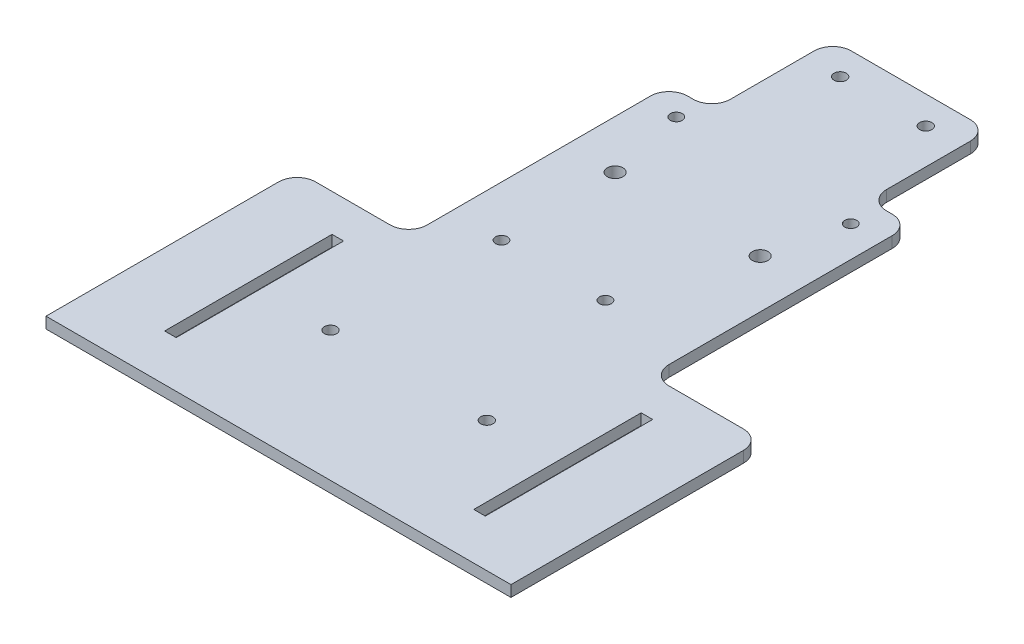
SolidWorks part; units mm, degrees
material "Balsa"
ref_plane "Front Plane" through (0, 0, 0) normal (0, 0, 1) x (1, 0, 0)
ref_plane "Top Plane" through (0, 0, 0) normal (0, 1, 0) x (1, 0, 0)
ref_plane "Right Plane" through (0, 0, 0) normal (1, 0, 0) x (0, 0, -1)
sketch "Sketch1" plane through (0, 0, 0) normal (0, 1, 0) x (1, 0, 0)
  line L0 (-41.55, -50) -> (41.55, -50) construction
  line L1 (-90, -85) -> (90, -85)
  line L2 (-90, -85) -> (-90, 85)
  line L3 (-90, 85) -> (90, 85)
  line L4 (90, -85) -> (90, 85)
  line L5 (-90, -85) -> (90, 85) construction
  line L6 (-90, 85) -> (90, -85) construction
  line L7 (0, -50) -> (0, 0) construction
  line L8 (40, -72.5) -> (43.1, -72.5)
  line L9 (40, -72.5) -> (40, -27.5)
  line L10 (40, -27.5) -> (43.1, -27.5)
  line L11 (43.1, -72.5) -> (43.1, -27.5)
  line L12 (40, -72.5) -> (43.1, -27.5) construction
  line L13 (40, -27.5) -> (43.1, -72.5) construction
  line L14 (-43.1, -72.5) -> (-40, -72.5)
  line L15 (-43.1, -72.5) -> (-43.1, -27.5)
  line L16 (-43.1, -27.5) -> (-40, -27.5)
  line L17 (-40, -72.5) -> (-40, -27.5)
  line L18 (-43.1, -72.5) -> (-40, -27.5) construction
  line L19 (-43.1, -27.5) -> (-40, -72.5) construction
  line L21 (90, -5) -> (62.5, -5)
  line L22 (90, -5) -> (90, -75)
  line L23 (90, -75) -> (62.5, -75)
  line L24 (62.5, -5) -> (62.5, -75)
  line L25 (-90, -5) -> (-62.5, -5)
  line L26 (-90, -5) -> (-90, -75)
  line L27 (-90, -75) -> (-62.5, -75)
  line L28 (-62.5, -5) -> (-62.5, -75)
  line L29 (-62.5, -5) -> (-90, -5)
  line L30 (-62.5, -5) -> (-62.5, 85)
  line L31 (-62.5, 85) -> (-90, 85)
  line L32 (-90, -5) -> (-90, 85)
  line L33 (90, -5) -> (62.5, -5)
  line L34 (90, -5) -> (90, 85)
  line L35 (90, 85) -> (62.5, 85)
  line L36 (62.5, -5) -> (62.5, 85)
  line L37 (90, -75) -> (62.5, -75)
  line L38 (90, -75) -> (90, -85)
  line L39 (90, -85) -> (62.5, -85)
  line L40 (62.5, -75) -> (62.5, -85)
  line L41 (-62.5, -75) -> (-90, -75)
  line L42 (-62.5, -75) -> (-62.5, -85)
  line L43 (-62.5, -85) -> (-90, -85)
  line L44 (-90, -75) -> (-90, -85)
  point P0 (0, 0)
  point P9 (0, -50)
  point P32 (-62.5, -40)
  dimension "D1" = 45
  dimension "D2" = 10
  dimension "D3" = 27.5
  dimension "D4" = 70
  dimension "D5" = 50
  dimension "D6" = 180
  dimension "D7" = 170
  dimension "D8" = 3.1
  dimension "D9" = 10
extrude "Boss-Extrude1" add sketch "Sketch1" along normal blind 3 contours L25 L28 L27 L2 L1 L4 L23 L24 L21 L3 L17 L14 L15 L16 L11 L8 L9 L10
sketch "Sketch3" plane through (0, 3, 0) normal (0, 1, 0) x (1, 0, 0)
  line L0 (-62.5, -85) -> (62.5, -85) construction
  line L5 (24.15, -6.1) -> (24.15, 46.1) construction
  line L6 (-24.15, -6.1) -> (24.15, -6.1) construction
  line L7 (-24.15, -6.1) -> (-24.15, 46.1) construction
  line L8 (-24.15, -6.1) -> (24.15, 46.1) construction
  line L10 (-24.15, 46.1) -> (24.15, 46.1) construction
  line L13 (-24.15, 46.1) -> (24.15, -6.1) construction
  line L15 (0, 20) -> (0, 46.1) construction
  circle A3 centre (-24.15, 46.1) radius 1.6
  circle A4 centre (24.15, 44.7) radius 1.6
  circle A5 centre (-18.95, -6.1) radius 1.6
  circle A6 centre (9, -6.1) radius 1.6
  point P39 (0, 20)
  dimension "D1" = 3.2
  dimension "D7" = 105
  dimension "D10" = 3.2
  dimension "D8" = 3.2
  dimension "D9" = 3.2
  dimension "D2" = 27.95
  dimension "D3" = 52.2
  dimension "D4" = 1.4
  dimension "D5" = 5.2
  dimension "D6" = 48.3
extrude "Cut-Extrude2" cut sketch "Sketch3" against normal blind 10
sketch "Sketch5" plane through (0, 0, 0) normal (0, -1, 0) x (1, 0, 0)
  line L0 (-62.5, -85) -> (62.5, -85) construction
  line L1 (0, 0) -> (0, -85) construction
  line L3 (-62.5, 85) -> (62.5, 85) construction
  circle A1 centre (11.5, -77.5) radius 1.65
  circle A2 centre (-11.5, -77.5) radius 1.65
  dimension "D2" = 3.3
  dimension "D1" = 162.5
  dimension "D4" = 11.5
extrude "Cut-Extrude4" cut sketch "Sketch5" against normal up to next
sketch "Sketch6" plane through (0, 3, 0) normal (0, 1, 0) x (1, 0, 0)
  line L0 (-21, -50) -> (21, -50) construction
  line L1 (-62.5, -85) -> (62.5, -85) construction
  circle A0 centre (21, -50) radius 1.65
  circle A1 centre (-21, -50) radius 1.65
  point P3 (0, -50)
  point P5 (-22.65, -50)
  point P8 (0, -85)
  point P9 (22.65, -50)
  point P11 (0.4138, -47.4383)
  point P13 (-0.15, -50)
  dimension "D1" = 3.3
  dimension "D2" = 42
  dimension "D3" = 35
extrude "Cut-Extrude5" cut sketch "Sketch6" against normal blind 10
sketch "Sketch8" plane through (0, 3, 0) normal (0, 1, 0) x (1, 0, 0)
  line L0 (62.5, 85) -> (62.5, -85) construction
  line L1 (62.5, 52.5) -> (32.5, 52.5)
  line L2 (62.5, 52.5) -> (62.5, -17.5)
  line L3 (62.5, -17.5) -> (32.5, -17.5)
  line L4 (32.5, 52.5) -> (32.5, -17.5)
  line L5 (-62.5, 85) -> (-62.5, -85) construction
  line L6 (-62.5, 52.5) -> (-32.5, 52.5)
  line L7 (-62.5, 52.5) -> (-62.5, -17.5)
  line L8 (-62.5, -17.5) -> (-32.5, -17.5)
  line L9 (-32.5, 52.5) -> (-32.5, -17.5)
  line L10 (40, -27.5) -> (43.1, -27.5) construction
  line L11 (-62.5, 85) -> (62.5, 85) construction
  line L12 (-62.5, 52.5) -> (-21, 52.5)
  line L13 (-62.5, 52.5) -> (-62.5, 85)
  line L14 (-62.5, 85) -> (-21, 85)
  line L15 (-21, 52.5) -> (-21, 85)
  line L17 (62.5, 52.5) -> (21, 52.5)
  line L18 (62.5, 52.5) -> (62.5, 85)
  line L19 (62.5, 85) -> (21, 85)
  line L20 (21, 52.5) -> (21, 85)
  point P17 (41.55, -27.5)
  line M31 (-62.5, 85) -> (-62.5, -85)
  line M33 (62.5, -85) -> (62.5, 85)
  line M34 (62.5, 85) -> (-62.5, 85)
  dimension "D1" = 65
  dimension "D2" = 70
  dimension "D3" = 10
  dimension "D4" = 42
extrude "Cut-Extrude6" cut sketch "Sketch8" against normal blind 10 contours L9 L6 L8 M31 | L12 L15 L6 M34 M31 | L20 L17 L1 M33 M34 | L1 L4 L3 M33
fillet "Fillet1" radius 5 10 edges at (62.5, 1.5, 17.5) (32.5, 1.5, -52.5) (32.5, 1.5, 17.5) (-32.5, 1.5, 17.5) (-62.5, 1.5, 17.5) (-32.5, 1.5, -52.5) (21, 1.5, -52.5) (21, 1.5, -85) (-21, 1.5, -85) (-21, 1.5, -52.5)
sketch "Sketch9" plane through (0, 3, 0) normal (0, 1, 0) x (1, 0, 0)
  line L0 (32.5, 25) -> (-32.5, 25) construction
  line L1 (32.5, 47.5) -> (32.5, -12.5) construction
  line L2 (-32.5, 47.5) -> (-32.5, -12.5) construction
  line L3 (0, 85) -> (0, 25) construction
  line L4 (-16, 85) -> (16, 85) construction
  circle A0 centre (19.5, 25) radius 2.1
  circle A1 centre (-19.5, 25) radius 2.1
  dimension "D1" = 4.2
  dimension "D2" = 39
  dimension "D3" = 60
extrude "Cut-Extrude7" cut sketch "Sketch9" against normal blind 10
